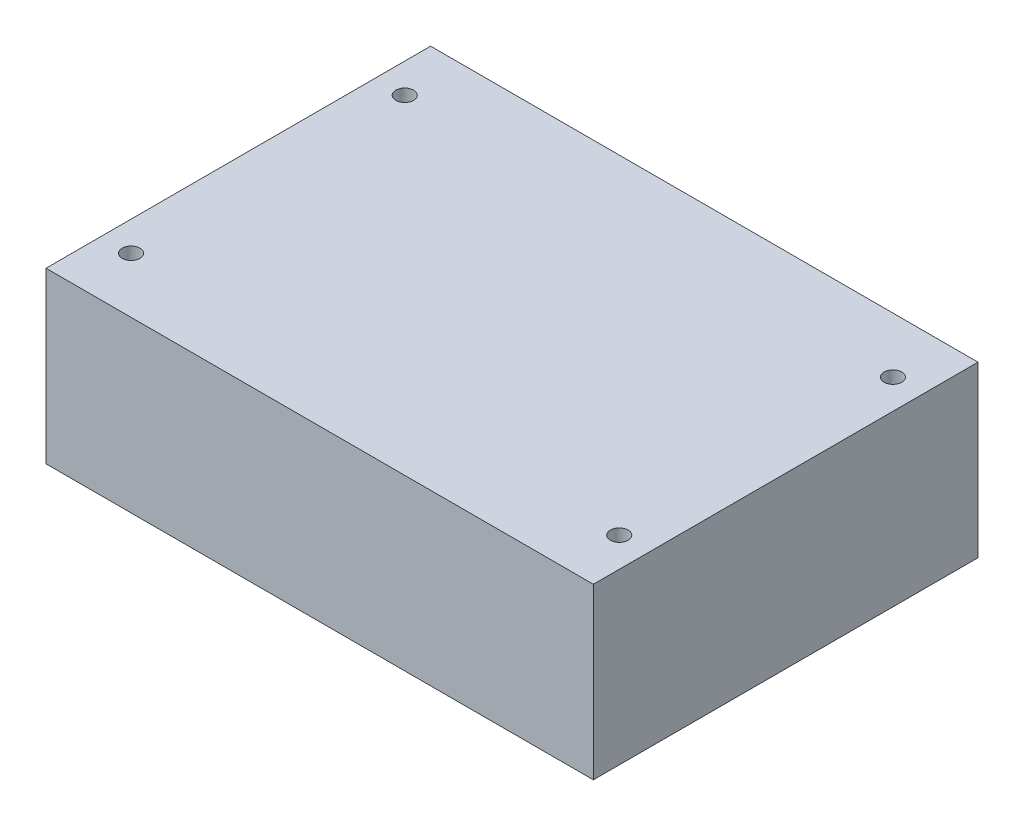
SolidWorks part; units mm, degrees
ref_plane "Alzado" through (0, 0, 0) normal (0, 0, 1) x (1, 0, 0)
ref_plane "Planta" through (0, 0, 0) normal (0, 1, 0) x (1, 0, 0)
ref_plane "Vista lateral" through (0, 0, 0) normal (1, 0, 0) x (0, 0, -1)
sketch "Croquis1" plane through (0, 11, 0) normal (0, 1, 0) x (1, 0, 0)
  line L1 (0, 0) -> (74, 0)
  line L2 (0, 0) -> (0, 52)
  line L3 (0, 52) -> (74, 52)
  line L4 (74, 0) -> (74, 52)
  point P4 (0, 0)
  dimension "D1" = 52
  dimension "D2" = 74
extrude "Saliente-Extruir1" add sketch "Croquis1" along normal blind 22.9 contours L2 L1 L4 L3
sketch "Croquis2" plane through (0, 33.9, 0) normal (0, 1, 0) x (1, 0, 0)
  line L0 (4, 44.5) -> (70, 44.5) construction
  line L2 (0, 52) -> (74, 52) construction
  line L3 (4, 44.5) -> (4, 7.5) construction
  line L4 (0, 0) -> (0, 52) construction
  circle A0 centre (4, 44.5) radius 1
  circle A1 centre (4, 7.5) radius 1
  circle A2 centre (70, 44.5) radius 1
  circle A3 centre (70, 7.5) radius 1
  point P8 (37, 52)
  point P11 (37, 44.5)
  point P15 (0, 26)
  point P16 (4, 26)
  dimension "D3" = 2
  dimension "D1" = 66
  dimension "D2" = 37
hole_wizard "Taladro de margen para M21" positions "Croquis3" profile "Croquis5" hole size "M2" standard "Ansi Metric"
sketch "Croquis3" plane through (0, 33.9, 0) normal (0, 1, 0) x (1, 0, 0)
  point P0 (4, 44.5)
  point P3 (70, 44.5)
  point P6 (70, 7.5)
  point P9 (4, 7.5)
sketch "Croquis5" plane through (4, 33.9, -44.5) normal (1, 0, 0) x (0, 0, 1)
  line L0 (0, 0) -> (0, 3.221)
  line L1 (0, 3.221) -> (1.2, 2.5)
  line L2 (1.2, 2.5) -> (1.2, 0)
  line L5 (1.2, 0) -> (0, 0)
  line L10 (0, 3.221) -> (-1.2, 2.5) construction
  line L11 (0, -6.35) -> (0, 107.95) construction
  dimension "Diámetro de taladro" = 2.4
  dimension "Profundidad de taladro" = 2.5
  dimension "Ángulo de perforador" = 118
